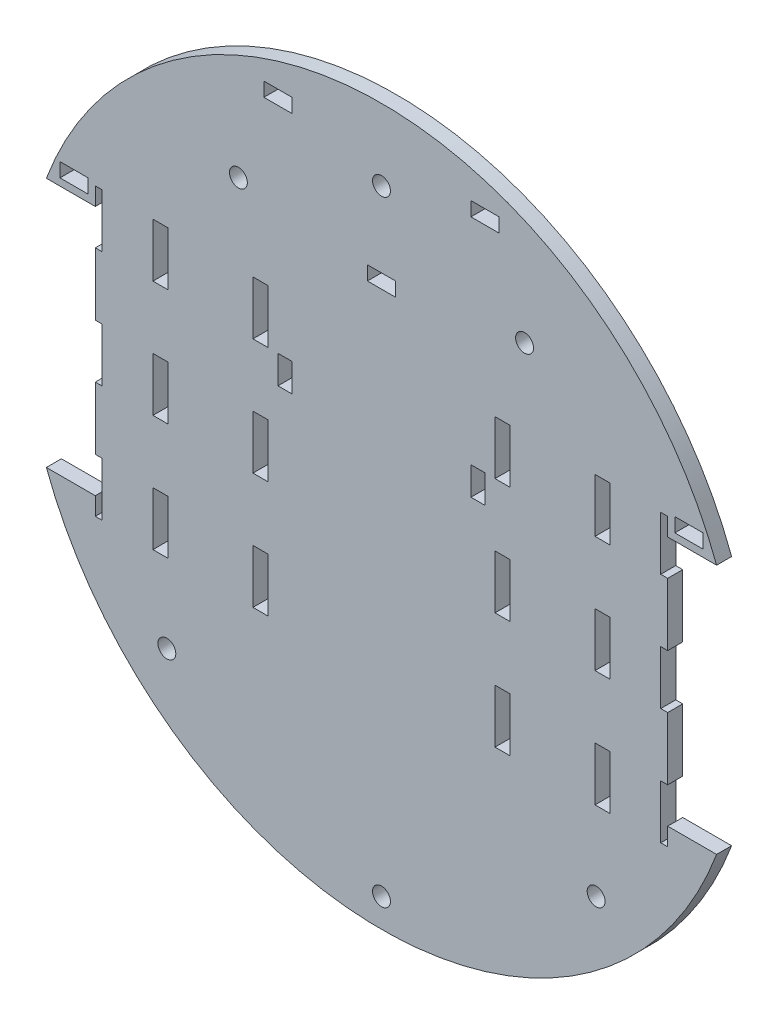
SolidWorks part; units mm, degrees
ref_plane "Front Plane" through (0, 0, 0) normal (0, 0, 1) x (1, 0, 0)
ref_plane "Top Plane" through (0, 0, 0) normal (0, 1, 0) x (1, 0, 0)
ref_plane "Right Plane" through (0, 0, 0) normal (1, 0, 0) x (0, 0, -1)
sketch "Sketch1" plane through (0, 0, 0) normal (0, 0, 1) x (1, 0, 0)
  line L0 (0, 0) -> (0, -50000) construction
  line L1 (0, 0) -> (50000, 0) construction
  circle A0 centre (0, 0) radius 127
  dimension "D1" = 254
extrude "Body" add sketch "Sketch1" along normal blind 5.334
sketch "Sketch7" plane through (0, 0, 5.334) normal (0, 0, 1) x (1, 0, 0)
  line L0 (0, 0) -> (-50000, 0) construction
  line L1 (0, 0) -> (0, 50000) construction
  line L2 (152.4, -44.45) -> (101.6, 44.45) construction
  line L3 (-152.4, 44.45) -> (-101.6, 44.45)
  line L4 (-152.4, 44.45) -> (-152.4, -44.45)
  line L5 (-152.4, -44.45) -> (-101.6, -44.45)
  line L6 (-101.6, 44.45) -> (-101.6, -44.45)
  line L7 (-152.4, 44.45) -> (-101.6, -44.45) construction
  line L8 (-152.4, -44.45) -> (-101.6, 44.45) construction
  line L9 (152.4, 44.45) -> (101.6, -44.45) construction
  line L10 (101.6, 44.45) -> (101.6, -44.45)
  line L11 (152.4, -44.45) -> (101.6, -44.45)
  line L12 (152.4, 44.45) -> (152.4, -44.45)
  line L13 (152.4, 44.45) -> (101.6, 44.45)
  circle A0 centre (0, 0) radius 127 construction
  point P5 (-127, 0)
  point P16 (127, 0)
  dimension "D1" = 88.9
  dimension "D2" = 101.6
extrude "WheelCuts" cut sketch "Sketch7" against normal through all
sketch "Sketch4" plane through (0, 0, 5.334) normal (0, 0, 1) x (1, 0, 0)
  line L0 (0, 0) -> (0, 50000) construction
  line L1 (-101.6, 50.8) -> (-99.1362, 50.8)
  line L2 (-101.6, 50.8) -> (-101.6, 31.75)
  line L3 (-101.6, 31.75) -> (-99.1362, 31.75)
  line L4 (-99.1362, 50.8) -> (-99.1362, 31.75)
  line L5 (0, 0) -> (50000, 0) construction
  line L6 (-99.1362, -50.8) -> (-99.1362, -31.75)
  line L7 (-101.6, 9.525) -> (-99.1362, 9.525)
  line L8 (-101.6, 9.525) -> (-101.6, -9.525)
  line L9 (-101.6, -9.525) -> (-99.1362, -9.525)
  line L10 (-99.1362, 9.525) -> (-99.1362, -9.525)
  line L11 (-101.6, 9.525) -> (-99.1362, -9.525) construction
  line L12 (-101.6, -9.525) -> (-99.1362, 9.525) construction
  line L13 (-101.6, -31.75) -> (-99.1362, -31.75)
  line L14 (-101.6, -50.8) -> (-101.6, -31.75)
  line L15 (-101.6, -50.8) -> (-99.1362, -50.8)
  line L16 (-81.1362, -50.8) -> (-81.1362, -31.75)
  line L17 (-75.8022, 50.8) -> (-81.1362, 50.8)
  line L18 (-75.8022, 50.8) -> (-75.8022, 31.75)
  line L19 (-75.8022, 31.75) -> (-81.1362, 31.75)
  line L20 (-81.1362, 50.8) -> (-81.1362, 31.75)
  line L21 (-81.1362, 9.525) -> (-75.8022, 9.525)
  line L22 (-81.1362, 9.525) -> (-81.1362, -9.525)
  line L23 (-81.1362, -9.525) -> (-75.8022, -9.525)
  line L24 (-75.8022, 9.525) -> (-75.8022, -9.525)
  line L25 (-75.8022, -31.75) -> (-81.1362, -31.75)
  line L26 (-75.8022, -50.8) -> (-75.8022, -31.75)
  line L27 (-75.8022, -50.8) -> (-81.1362, -50.8)
  line L28 (-40.3, -50.8) -> (-40.3, -31.75)
  line L29 (-45.634, 50.8) -> (-40.3, 50.8)
  line L30 (-45.634, 50.8) -> (-45.634, 31.75)
  line L31 (-45.634, 31.75) -> (-40.3, 31.75)
  line L32 (-40.3, 50.8) -> (-40.3, 31.75)
  line L33 (-40.3, 9.525) -> (-45.634, 9.525)
  line L34 (-40.3, 9.525) -> (-40.3, -9.525)
  line L35 (-40.3, -9.525) -> (-45.634, -9.525)
  line L36 (-45.634, 9.525) -> (-45.634, -9.525)
  line L37 (-45.634, -31.75) -> (-40.3, -31.75)
  line L38 (-45.634, -50.8) -> (-45.634, -31.75)
  line L39 (-45.634, -50.8) -> (-40.3, -50.8)
  line L42 (45.634, -50.8) -> (40.3, -50.8)
  line L43 (45.634, -50.8) -> (45.634, -31.75)
  line L44 (45.634, -31.75) -> (40.3, -31.75)
  line L45 (45.634, 9.525) -> (45.634, -9.525)
  line L46 (40.3, -9.525) -> (45.634, -9.525)
  line L47 (40.3, 9.525) -> (40.3, -9.525)
  line L48 (40.3, 9.525) -> (45.634, 9.525)
  line L49 (40.3, 50.8) -> (40.3, 31.75)
  line L50 (45.634, 31.75) -> (40.3, 31.75)
  line L51 (45.634, 50.8) -> (45.634, 31.75)
  line L52 (45.634, 50.8) -> (40.3, 50.8)
  line L53 (40.3, -50.8) -> (40.3, -31.75)
  line L54 (75.8022, -50.8) -> (81.1362, -50.8)
  line L55 (75.8022, -50.8) -> (75.8022, -31.75)
  line L56 (75.8022, -31.75) -> (81.1362, -31.75)
  line L57 (75.8022, 9.525) -> (75.8022, -9.525)
  line L58 (81.1362, -9.525) -> (75.8022, -9.525)
  line L59 (81.1362, 9.525) -> (81.1362, -9.525)
  line L60 (81.1362, 9.525) -> (75.8022, 9.525)
  line L61 (81.1362, 50.8) -> (81.1362, 31.75)
  line L62 (75.8022, 31.75) -> (81.1362, 31.75)
  line L63 (75.8022, 50.8) -> (75.8022, 31.75)
  line L64 (75.8022, 50.8) -> (81.1362, 50.8)
  line L65 (81.1362, -50.8) -> (81.1362, -31.75)
  line L66 (101.6, -50.8) -> (99.1362, -50.8)
  line L67 (101.6, -50.8) -> (101.6, -31.75)
  line L68 (101.6, -31.75) -> (99.1362, -31.75)
  line L69 (99.1362, 9.525) -> (99.1362, -9.525)
  line L70 (101.6, -9.525) -> (99.1362, -9.525)
  line L71 (101.6, 9.525) -> (101.6, -9.525)
  line L72 (101.6, 9.525) -> (99.1362, 9.525)
  line L73 (99.1362, -50.8) -> (99.1362, -31.75)
  line L74 (99.1362, 50.8) -> (99.1362, 31.75)
  line L75 (101.6, 31.75) -> (99.1362, 31.75)
  line L76 (101.6, 50.8) -> (101.6, 31.75)
  line L77 (101.6, 50.8) -> (99.1362, 50.8)
  point P9 (-100.3681, 0)
  point P78 (100.3681, 0)
  dimension "D1" = 2.4638
  dimension "D2" = 19.05
  dimension "D3" = 99.1362
  dimension "D4" = 50.8
  dimension "D5" = 19.05
  dimension "D6" = 2.4638
  dimension "D7" = 75.8022
  dimension "D8" = 5.334
  dimension "D9" = 40.3
  dimension "D10" = 5.334
  dimension "D11" = 99.1362
  dimension "D12" = 22.225
  dimension "D13" = 22.225
  dimension "D14" = 63.5
  dimension "D15" = 30.1682
extrude "MotorMounts" cut sketch "Sketch4" against normal through all
sketch "Sketch5" plane through (0, 0, 5.334) normal (0, 0, 1) x (1, 0, 0)
  line L0 (0, 0) -> (0, -50000) construction
  line L1 (0, 0) -> (-50000, 0) construction
  circle A0 centre (0, -116.84) radius 3.175
  circle A1 centre (0, 101.6) radius 3.175
  dimension "D1" = 6.35
  dimension "D3" = 6.35
  dimension "D2" = 116.84
  dimension "D4" = 101.6
extrude "Castor" cut sketch "Sketch5" against normal through all
sketch "Sketch6" plane through (0, 0, 5.334) normal (0, 0, 1) x (1, 0, 0)
  line L0 (0, 0) -> (50000, 0) construction
  line L1 (0, 0) -> (0, 50000) construction
  circle A0 centre (-76.2, -78.74) radius 3.175
  circle A1 centre (-50.8, 78.74) radius 3.175
  circle A2 centre (76.2, -78.74) radius 3.175
  circle A3 centre (50.8, 78.74) radius 3.175
  dimension "D3" = 6.35
  dimension "D4" = 6.35
  dimension "D1" = 50.8
  dimension "D2" = 76.2
  dimension "D5" = 78.74
  dimension "D6" = 78.74
extrude "BoltHoles" cut sketch "Sketch6" against normal through all
sketch "Sketch3" plane through (0, 0, 5.334) normal (0, 0, 1) x (1, 0, 0)
  line L0 (0, 0) -> (-50000, 0) construction
  line L1 (0, 0) -> (0, 50000) construction
  line L2 (-41.75, 112.95) -> (-31.75, 112.95)
  line L3 (-114.14, 51.99) -> (-104.14, 51.99)
  line L4 (-114.14, 51.99) -> (-114.14, 46.99)
  line L5 (-114.14, 46.99) -> (-104.14, 46.99)
  line L6 (-104.14, 51.99) -> (-104.14, 46.99)
  line L7 (-41.75, 112.95) -> (-41.75, 107.95)
  line L8 (-41.75, 107.95) -> (-31.75, 107.95)
  line L9 (-31.75, 112.95) -> (-31.75, 107.95)
  line L10 (41.75, 112.95) -> (41.75, 107.95)
  line L11 (-5, 74.85) -> (5, 74.85)
  line L12 (-5, 74.85) -> (-5, 69.85)
  line L13 (-5, 69.85) -> (5, 69.85)
  line L14 (5, 74.85) -> (5, 69.85)
  line L15 (-5, 74.85) -> (5, 69.85) construction
  line L16 (-5, 69.85) -> (5, 74.85) construction
  line L17 (31.75, 112.95) -> (31.75, 107.95)
  line L18 (41.75, 107.95) -> (31.75, 107.95)
  line L19 (41.75, 112.95) -> (31.75, 112.95)
  line L20 (104.14, 51.99) -> (104.14, 46.99)
  line L21 (114.14, 46.99) -> (104.14, 46.99)
  line L22 (114.14, 51.99) -> (114.14, 46.99)
  line L23 (114.14, 51.99) -> (104.14, 51.99)
  line L24 (36.75, 31.75) -> (36.75, 21.75)
  line L25 (-31.75, 31.75) -> (-36.75, 31.75)
  line L26 (-31.75, 31.75) -> (-31.75, 21.75)
  line L27 (-31.75, 21.75) -> (-36.75, 21.75)
  line L28 (-36.75, 31.75) -> (-36.75, 21.75)
  line L29 (31.75, 21.75) -> (36.75, 21.75)
  line L30 (31.75, 31.75) -> (31.75, 21.75)
  line L31 (31.75, 31.75) -> (36.75, 31.75)
  point P13 (0, 72.35)
  dimension "D1" = 10
  dimension "D2" = 5
  dimension "D3" = 104.14
  dimension "D4" = 46.99
  dimension "D5" = 107.95
  dimension "D6" = 31.75
  dimension "D7" = 10
  dimension "D8" = 5
  dimension "D9" = 69.85
  dimension "D10" = 10
  dimension "D11" = 5
  dimension "D12" = 5
  dimension "D13" = 10
  dimension "D14" = 31.75
  dimension "D15" = 31.75
extrude "TapeSensCutOut" cut sketch "Sketch3" against normal through all
